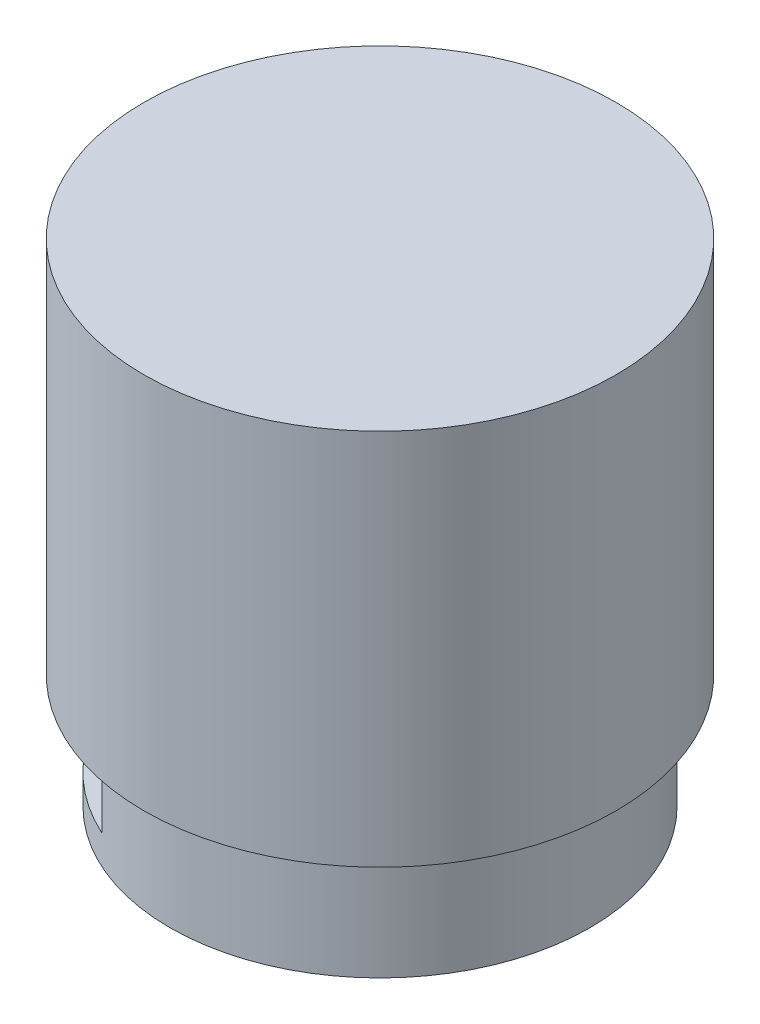
SolidWorks part; units mm, degrees
ref_plane "Front Plane" through (0, 0, 0) normal (0, 0, 1) x (1, 0, 0)
ref_plane "Top Plane" through (0, 0, 0) normal (0, 1, 0) x (1, 0, 0)
ref_plane "Right Plane" through (0, 0, 0) normal (1, 0, 0) x (0, 0, -1)
sketch "Sketch4" plane through (0, 0, 0) normal (0, 1, 0) x (1, 0, 0)
  circle A0 centre (0, 0) radius 22.25
  circle A1 centre (0, 0) radius 15.275
  circle A2 centre (0, 0) radius 20.25 construction
  dimension "D1" = 30.55
  dimension "D2" = 40.5
  dimension "D3" = 2
sketch "Sketch5" plane through (0, 0, 0) normal (0, 1, 0) x (1, 0, 0)
  circle A0 centre (0, 0) radius 15.275
  circle A1 centre (0, 0) radius 22.25
  circle A2 centre (0, 0) radius 22.25 construction
  circle A3 centre (0, 0) radius 15.275 construction
extrude "Boss-Extrude1" add sketch "Sketch5" along normal blind 3.1
sketch "Sketch6" plane through (0, 3.1, 0) normal (0, 1, 0) x (1, 0, 0)
  circle A0 centre (0, 0) radius 20.25
  circle A1 centre (0, 0) radius 22.25
  circle A2 centre (0, 0) radius 22.25 construction
  circle A3 centre (0, 0) radius 20.25 construction
extrude "Boss-Extrude2" add sketch "Sketch6" along normal blind 6
sketch "Sketch7" plane through (0, 9.1, 0) normal (0, 1, 0) x (1, 0, 0)
  circle A0 centre (0, 0) radius 22.25
  circle A1 centre (0, 0) radius 22.25 construction
extrude "Boss-Extrude3" add sketch "Sketch7" along normal blind 3
sketch "Sketch8" plane through (0, 12.1, 0) normal (0, 1, 0) x (1, 0, 0)
  circle A0 centre (0, 0) radius 25
  dimension "D1" = 50
extrude "Boss-Extrude4" add sketch "Sketch8" along normal blind 40
sketch "Sketch9" plane through (0, 3.1, 0) normal (0, 1, 0) x (1, 0, 0)
  line L1 (0, 20.25) -> (-22.25, 20.25)
  line L2 (0, 20.25) -> (0, -20.25)
  line L3 (0, -20.25) -> (-22.25, -20.25)
  line L4 (-22.25, 20.25) -> (-22.25, -20.25)
  circle A0 centre (0, 0) radius 20.25 construction
  circle A2 centre (0, 0) radius 22.25 construction
extrude "Cut-Extrude1" cut sketch "Sketch9" along normal up to surface (6 mm away) up to face at (0, 9.1, 20.25)
equation "\"Diameter\" = 50mm"
equation "\"D1@Sketch8\"=\"Diameter\""
